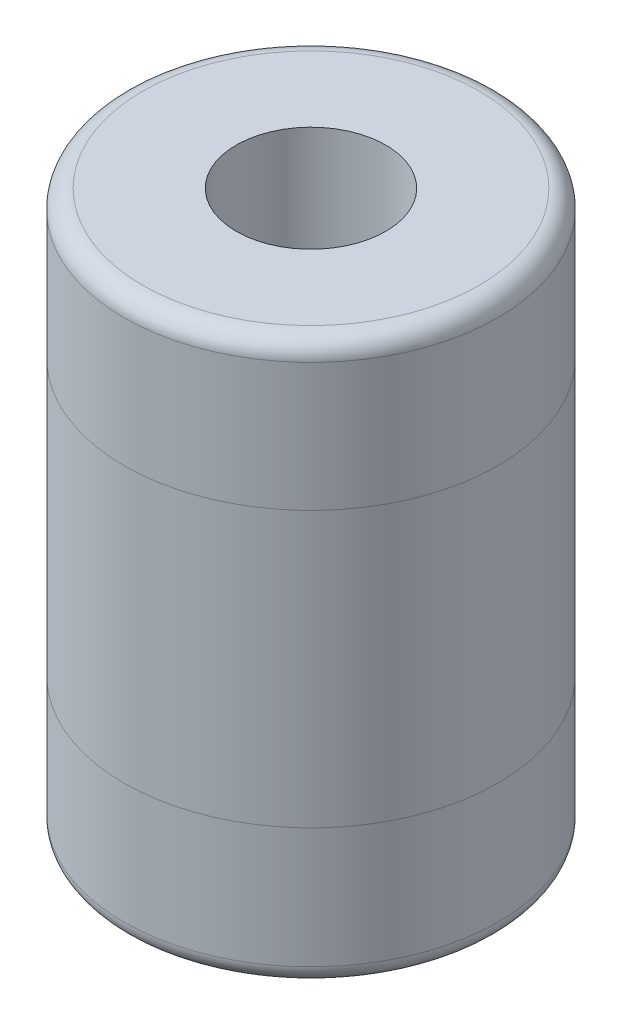
SolidWorks part; units mm, degrees
ref_plane "Front Plane" through (0, 0, 0) normal (0, 0, 1) x (1, 0, 0)
ref_plane "Top Plane" through (0, 0, 0) normal (0, 1, 0) x (1, 0, 0)
ref_plane "Right Plane" through (0, 0, 0) normal (1, 0, 0) x (0, 0, -1)
sketch "Sketch1" plane through (0, 0, 0) normal (0, 1, 0) x (1, 0, 0)
  circle A0 centre (0, 0) radius 10
  dimension "D1" = 20
extrude "Boss-Extrude1" add sketch "Sketch1" along normal mid plane 30
sketch "Sketch2" plane through (0, 15, 0) normal (0, 1, 0) x (1, 0, 0)
  circle A0 centre (0, 0) radius 4
  dimension "D1" = 8
extrude "Cut-Extrude1" cut sketch "Sketch2" against normal through all
sketch "Sketch3" plane through (0, -15, 0) normal (0, -1, 0) x (1, 0, 0)
  circle A0 centre (0, 0) radius 4
  dimension "D1" = 8
extrude "Cut-Extrude2" [suppressed] cut sketch "Sketch3" against normal blind 20
sketch "Sketch4" plane through (0, 0, 0) normal (0, 0, 1) x (1, 0, 0)
  line L1 (-17.7837, 7.1454) -> (18.0476, 7.1454)
  line L2 (-17.7837, 7.1454) -> (-17.7837, -7.5631)
  line L3 (-17.7837, -7.5631) -> (18.0476, -7.5631)
  line L4 (18.0476, 7.1454) -> (18.0476, -7.5631)
split line "Split Line1"
fillet "Fillet1" radius 1 2 edges at (0, -15, 10) (0, 15, 10)
